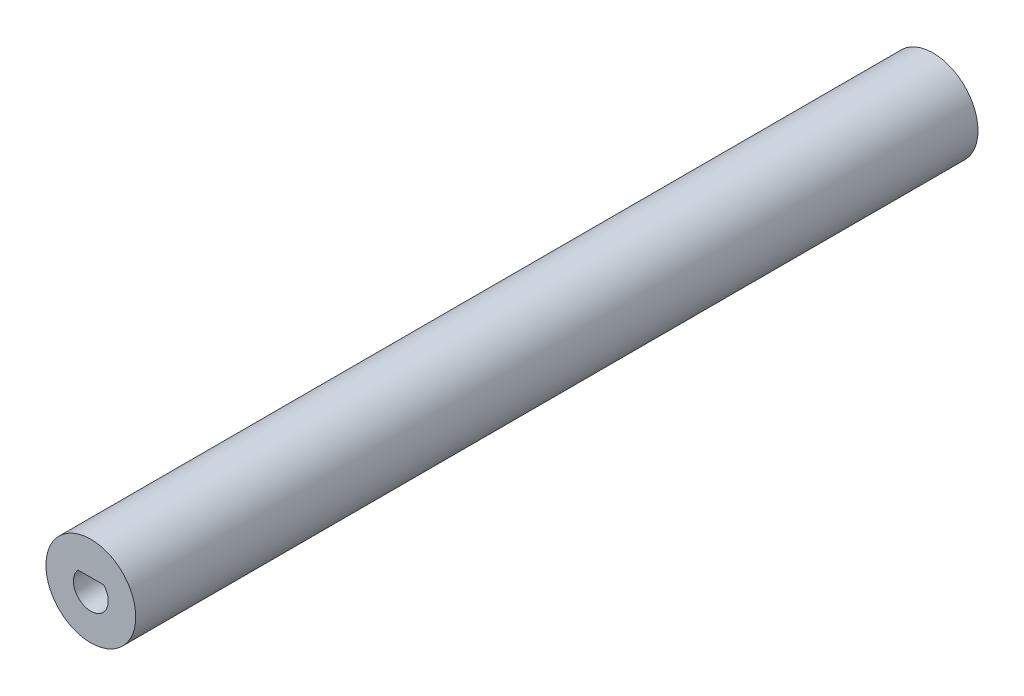
SolidWorks part; units mm, degrees
ref_plane "Ön Düzlem" through (0, 0, 0) normal (0, 0, 1) x (1, 0, 0)
ref_plane "Üst Düzlem" through (0, 0, 0) normal (0, 1, 0) x (1, 0, 0)
ref_plane "Sağ Düzlem" through (0, 0, 0) normal (1, 0, 0) x (0, 0, -1)
sketch "Çizim1" plane through (0, 0, 0) normal (0, 0, 1) x (1, 0, 0)
  circle A0 centre (0, 0) radius 4
  dimension "D1" = 8
extrude "Yükseklik-Ekstrüzyon1" add sketch "Çizim1" along normal blind 75
sketch "Çizim2" plane through (0, 0, 75) normal (0, 0, 1) x (1, 0, 0)
  line L0 (-1.1402, 1.05) -> (1.1402, 1.05)
  arc A0 (-1.1402, 1.05) -> (1.1402, 1.05) centre (0, 0) ccw
  dimension "D1" = 3.1
extrude "Kes-Ekstrüzyon1" cut sketch "Çizim2" against normal blind 104
